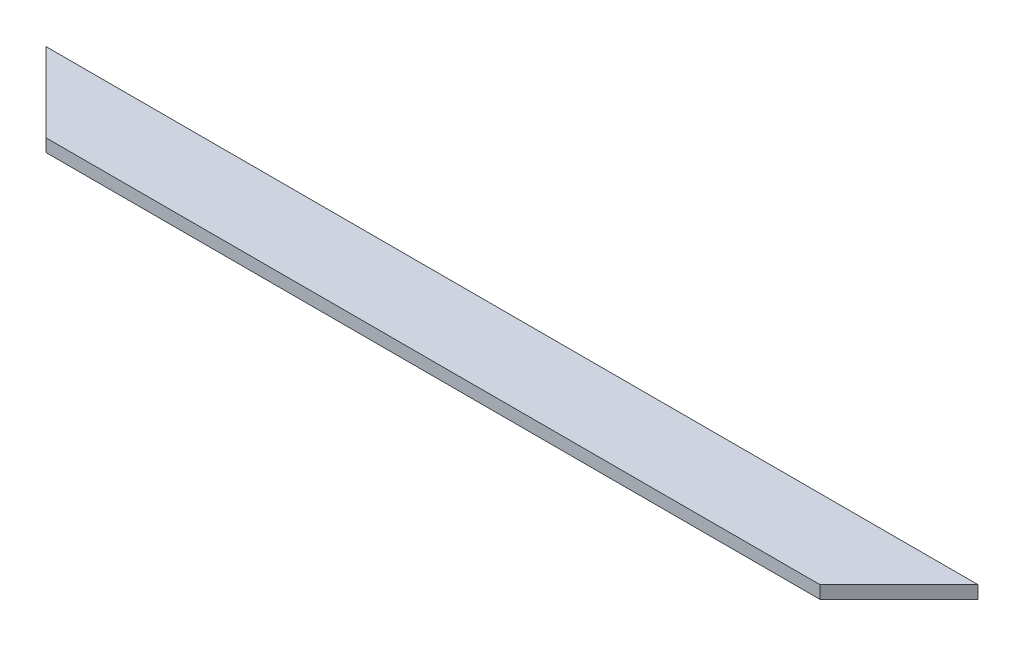
SolidWorks part; units mm, degrees
material "PE High Density"
ref_plane "Front Plane" through (0, 0, 0) normal (0, 0, 1) x (1, 0, 0)
ref_plane "Top Plane" through (0, 0, 0) normal (0, 1, 0) x (1, 0, 0)
ref_plane "Right Plane" through (0, 0, 0) normal (1, 0, 0) x (0, 0, -1)
sketch "Sketch1" plane through (0, 0, 0) normal (0, 1, 0) x (1, 0, 0)
  line L0 (-756.8043, 301.3137) -> (-623.4543, 301.3137) construction
  line L1 (-756.8043, 301.3137) -> (816.4082, 301.3137)
  line L3 (-623.4543, 167.9637) -> (683.0582, 167.9637)
  line L5 (-623.4543, 301.3137) -> (-623.4543, 167.9637) construction
  line L6 (683.0582, 301.3137) -> (683.0582, 167.9637) construction
  line L7 (-756.8043, 301.3137) -> (-623.4543, 167.9637)
  line L8 (816.4082, 301.3137) -> (683.0582, 167.9637)
  dimension "D1" = 1573.2125
  dimension "D3" = 133.35
  dimension "D4" = 133.35
extrude "Boss-Extrude1" add sketch "Sketch1" along normal blind 21.59
